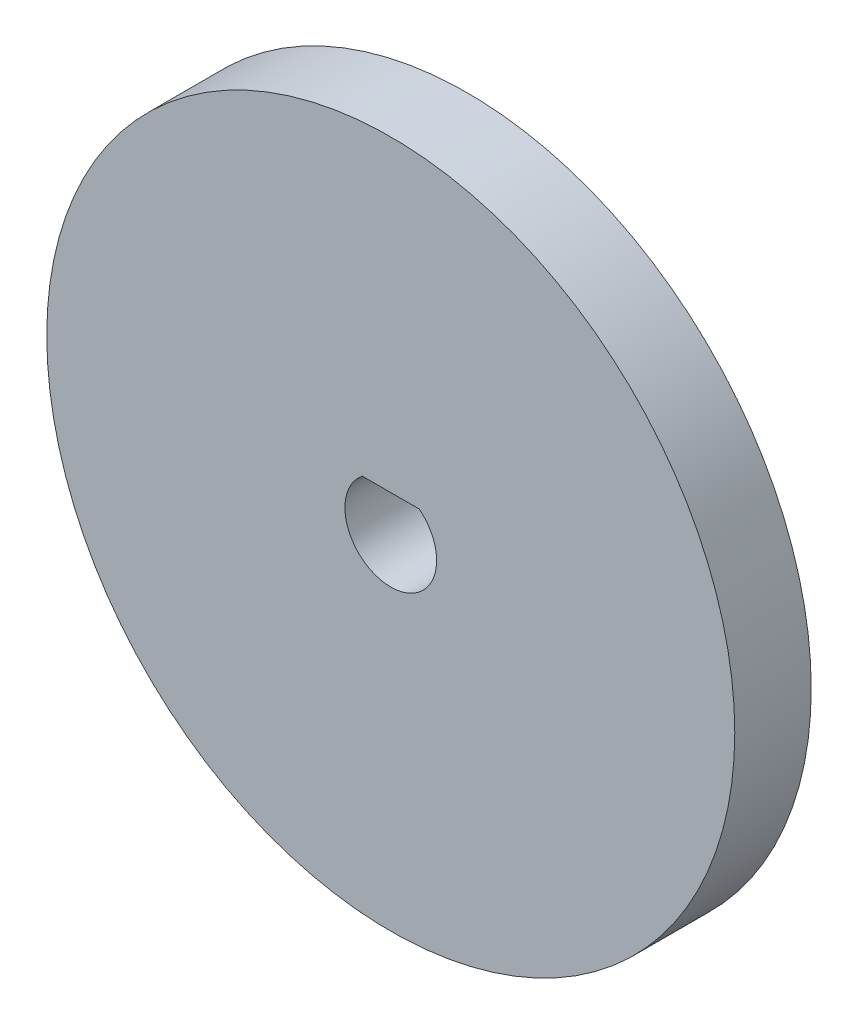
SolidWorks part; units mm, degrees
ref_plane "Front Plane" through (0, 0, 0) normal (0, 0, 1) x (1, 0, 0)
ref_plane "Top Plane" through (0, 0, 0) normal (0, 1, 0) x (1, 0, 0)
ref_plane "Right Plane" through (0, 0, 0) normal (1, 0, 0) x (0, 0, -1)
sketch "Sketch1" plane through (0, 0, 0) normal (0, 0, 1) x (1, 0, 0)
  line L0 (-1.8648, 2.35) -> (1.8648, 2.35)
  circle A0 centre (0, 0) radius 22.5
  circle A1 centre (0, 0) radius 3
  dimension "D1" = 45
  dimension "D2" = 6
  dimension "D3" = 2.35
extrude "Boss-Extrude1" add sketch "Sketch1" along normal blind 5 contours A0 A1 | L0 A1
